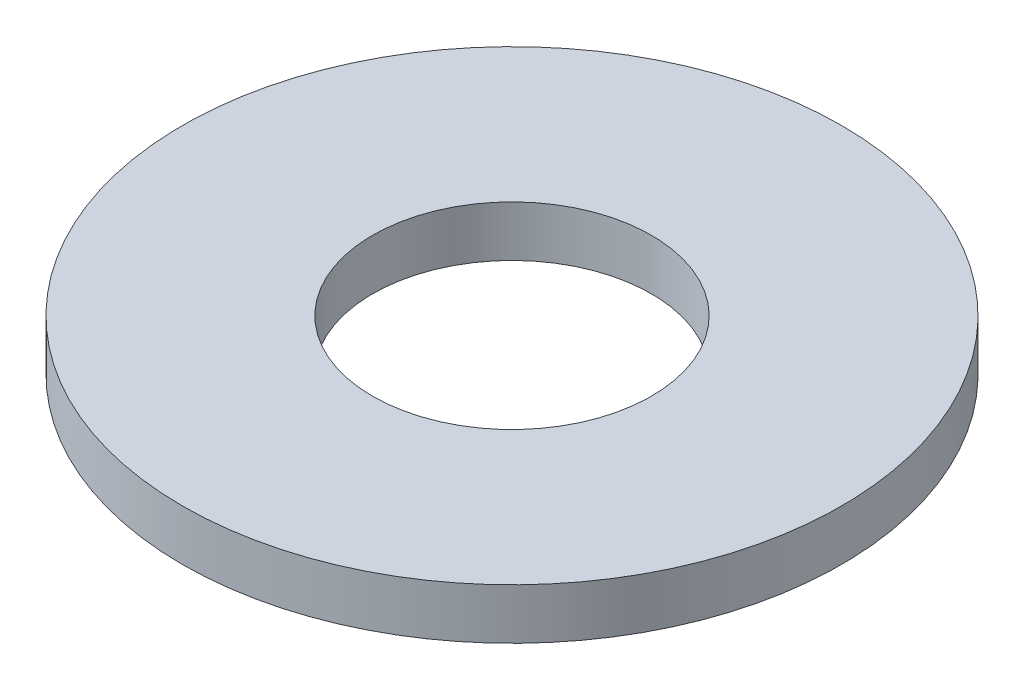
SolidWorks part; units mm, degrees
ref_plane "Front Plane" through (0, 0, 0) normal (0, 0, 1) x (1, 0, 0)
ref_plane "Top Plane" through (0, 0, 0) normal (0, 1, 0) x (1, 0, 0)
ref_plane "Right Plane" through (0, 0, 0) normal (1, 0, 0) x (0, 0, -1)
sketch "Sketch1" plane through (0, 0, 0) normal (0, 1, 0) x (1, 0, 0)
  circle A0 centre (0, 0) radius 13
  circle A1 centre (0, 0) radius 5.5
  dimension "D1" = 26
  dimension "D2" = 11
extrude "Boss-Extrude1" add sketch "Sketch1" along normal blind 2
